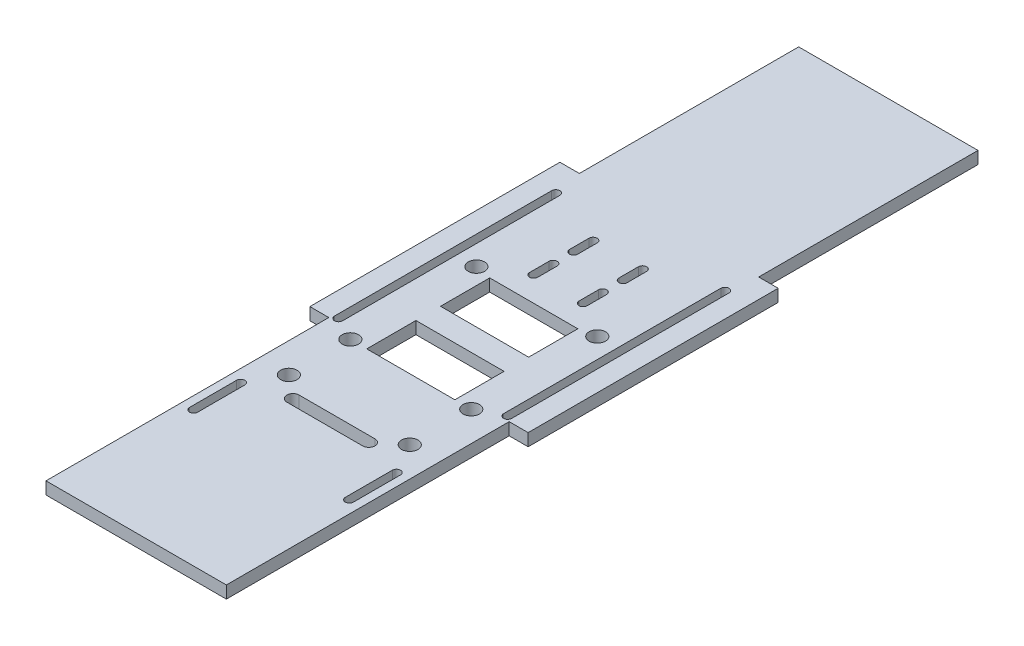
SolidWorks part; units mm, degrees
ref_plane "Front Plane" through (0, 0, 0) normal (0, 0, 1) x (1, 0, 0)
ref_plane "Top Plane" through (0, 0, 0) normal (0, 1, 0) x (1, 0, 0)
ref_plane "Right Plane" through (0, 0, 0) normal (1, 0, 0) x (0, 0, -1)
sketch "Sketch1" plane through (0, 0, 0) normal (0, 1, 0) x (1, 0, 0)
  line L1 (9.5525, -5.1674) -> (51.8197, -5.1674)
  line L2 (9.5525, -5.1674) -> (9.5525, 43.2514)
  line L3 (9.5525, 43.2514) -> (51.8197, 43.2514)
  line L4 (51.8197, -5.1674) -> (51.8197, 43.2514)
  line L5 (13.3228, 43.2514) -> (48.0494, 43.2514)
  line L6 (13.3228, 43.2514) -> (13.3228, 85.717)
  line L7 (13.3228, 85.717) -> (48.0494, 85.717)
  line L8 (48.0494, 43.2514) -> (48.0494, 85.717)
  line L9 (22.1533, -6.7549) -> (39.2189, -6.7549)
  line L10 (13.2236, -5.1674) -> (48.1486, -5.1674)
  line L11 (13.2236, -5.1674) -> (13.2236, -59.9361)
  line L12 (13.2236, -59.9361) -> (48.1486, -59.9361)
  line L13 (48.1486, -5.1674) -> (48.1486, -59.9361)
  line L14 (22.1533, -6.7549) -> (22.1533, 2.7701)
  line L15 (22.1533, 2.7701) -> (39.2189, 2.7701)
  line L16 (39.2189, -6.7549) -> (39.2189, 2.7701)
  line L20 (35.4697, 21.8201) -> (35.4697, 25.5901) construction
  line L21 (23.3439, -22.233) -> (38.0283, -22.233) construction
  line L22 (34.676, 21.8201) -> (34.676, 25.5901)
  line L23 (36.2635, 21.8201) -> (36.2635, 25.5901)
  line L24 (47.0572, -4.3736) -> (47.0572, 37.6951) construction
  line L25 (23.3439, -21.0424) -> (38.0283, -21.0424)
  line L26 (23.3439, -23.4236) -> (38.0283, -23.4236)
  line L27 (22.1533, 7.5326) -> (39.2189, 7.5326)
  line L28 (46.2635, -4.3736) -> (46.2635, 37.6951)
  line L29 (47.851, -4.3736) -> (47.851, 37.6951)
  line L30 (22.1533, 7.5326) -> (22.1533, 17.0576)
  line L31 (22.1533, 17.0576) -> (39.2189, 17.0576)
  line L32 (39.2189, 7.5326) -> (39.2189, 17.0576)
  line L33 (45.7674, -33.7424) -> (45.7674, -24.6143) construction
  line L34 (30.6861, 85.717) -> (30.6861, -59.9361)
  line L35 (44.9736, -33.7424) -> (44.9736, -24.6143)
  line L36 (46.5611, -33.7424) -> (46.5611, -24.6143)
  line L37 (35.4697, 29.5588) -> (35.4697, 33.3287) construction
  line L38 (34.676, 29.5588) -> (34.676, 33.3287)
  line L39 (36.2635, 29.5588) -> (36.2635, 33.3287)
  line L40 (25.9025, 29.5588) -> (25.9025, 33.3287) construction
  line L41 (26.6963, 29.5588) -> (26.6963, 33.3287)
  line L42 (25.1088, 29.5588) -> (25.1088, 33.3287)
  line L43 (25.9025, 21.8201) -> (25.9025, 25.5901) construction
  line L44 (26.6963, 21.8201) -> (26.6963, 25.5901)
  line L45 (25.1088, 21.8201) -> (25.1088, 25.5901)
  line L46 (14.315, -4.3736) -> (14.315, 37.6951) construction
  line L47 (15.1088, -4.3736) -> (15.1088, 37.6951)
  line L48 (13.5213, -4.3736) -> (13.5213, 37.6951)
  line L49 (15.6049, -33.7424) -> (15.6049, -24.6143) construction
  line L50 (16.3986, -33.7424) -> (16.3986, -24.6143)
  line L51 (14.8111, -33.7424) -> (14.8111, -24.6143)
  circle A0 centre (42.3939, -6.7549) radius 1.5875
  arc A1 (34.676, 21.8201) -> (36.2635, 21.8201) centre (35.4697, 21.8201) ccw
  arc A2 (36.2635, 25.5901) -> (34.676, 25.5901) centre (35.4697, 25.5901) ccw
  arc A3 (23.3439, -21.0424) -> (23.3439, -23.4236) centre (23.3439, -22.233) ccw
  arc A4 (38.0283, -23.4236) -> (38.0283, -21.0424) centre (38.0283, -22.233) ccw
  arc A5 (46.2635, -4.3736) -> (47.851, -4.3736) centre (47.0572, -4.3736) ccw
  arc A6 (47.851, 37.6951) -> (46.2635, 37.6951) centre (47.0572, 37.6951) ccw
  arc A7 (44.9736, -33.7424) -> (46.5611, -33.7424) centre (45.7674, -33.7424) ccw
  arc A8 (46.5611, -24.6143) -> (44.9736, -24.6143) centre (45.7674, -24.6143) ccw
  arc A9 (34.676, 29.5588) -> (36.2635, 29.5588) centre (35.4697, 29.5588) ccw
  arc A10 (36.2635, 33.3287) -> (34.676, 33.3287) centre (35.4697, 33.3287) ccw
  circle A11 centre (42.3939, 17.6529) radius 1.5875
  circle A12 centre (42.3939, -18.6611) radius 1.5875
  arc A13 (26.6963, 29.5588) -> (25.1088, 29.5588) centre (25.9025, 29.5588) cw
  arc A14 (25.1088, 33.3287) -> (26.6963, 33.3287) centre (25.9025, 33.3287) cw
  arc A15 (26.6963, 21.8201) -> (25.1088, 21.8201) centre (25.9025, 21.8201) cw
  arc A16 (25.1088, 25.5901) -> (26.6963, 25.5901) centre (25.9025, 25.5901) cw
  circle A17 centre (18.9783, 17.6529) radius 1.5875
  arc A18 (15.1088, -4.3736) -> (13.5213, -4.3736) centre (14.315, -4.3736) cw
  arc A19 (13.5213, 37.6951) -> (15.1088, 37.6951) centre (14.315, 37.6951) cw
  circle A20 centre (18.9783, -6.7549) radius 1.5875
  circle A21 centre (18.9783, -18.6611) radius 1.5875
  arc A22 (16.3986, -33.7424) -> (14.8111, -33.7424) centre (15.6049, -33.7424) cw
  arc A23 (14.8111, -24.6143) -> (16.3986, -24.6143) centre (15.6049, -24.6143) cw
  point P8 (30.6861, 43.2514)
  point P9 (30.6861, -5.1674)
  point P18 (22.1533, -22.233)
  point P21 (36.2635, 23.7051)
  point P24 (35.4697, 23.7051)
  point P32 (30.6861, -22.233)
  point P39 (30.6861, -6.7549)
  point P40 (47.0572, 16.6607)
  point P46 (45.7674, -29.1783)
  point P51 (30.6861, 7.5326)
  point P53 (35.4697, 21.0264)
  point P59 (0, 0)
  point P60 (0, 0)
  point P63 (29.506, 42.1053)
  point P64 (35.4697, 31.4438)
  point P69 (28.7122, 39.4266)
  point P70 (0, 0)
  point P71 (0, 0)
  point P72 (35.4697, 28.7651)
  point P73 (35.4697, 26.3838)
  point P76 (0, 0)
  point P77 (0, 0)
  point P78 (0, 0)
  point P81 (0, 0)
  point P82 (41.0049, -15.5365)
  point P83 (39.2189, -22.233)
  point P86 (25.9025, 31.4438)
  point P93 (25.9025, 23.7051)
  point P102 (14.315, 16.6607)
  point P113 (15.6049, -29.1783)
  dimension "D9" = 3.175
  dimension "D11" = 1.5875
  dimension "D13" = 17.0656
  dimension "D10" = 3.7699
  dimension "D20" = 3.9688
  dimension "D25" = 1.1906
  dimension "D27" = 21.2328
  dimension "D28" = 8.7312
  dimension "D1" = 48.4187
  dimension "D2" = 42.2672
  dimension "D3" = 42.4656
  dimension "D4" = 34.7266
  dimension "D5" = 54.7687
  dimension "D6" = 34.925
  dimension "D7" = 9.525
  dimension "D8" = 17.0656
  dimension "D12" = 2.3813
  dimension "D14" = 1.5875
  dimension "D15" = 42.0687
  dimension "D16" = 3.9688
  dimension "D17" = 3.175
  dimension "D18" = 14.2875
  dimension "D19" = 4.7625
  dimension "D21" = 10
  dimension "D22" = 1.5875
  dimension "D23" = 1.5875
  dimension "D24" = 9.1281
  dimension "D26" = 2.3813
extrude "Boss-Extrude2" add sketch "Sketch1" along normal mid plane 2.3813 contours L1 A20 L10 L11 L12 L34 L26 A3 L25 L9 L14 A21 L51 A23 L50 A22 | A4 L26 L34 L12 L13 L1 L10 A0 L16 L9 L25 A12 A8 L36 A7 L35 | L48 A19 L47 A18 L10 L1 L14 L15 L34 L27 L30 L31 L3 L2 L45 A16 L44 A15 L42 A14 L41 A13 A17 | A6 L29 A5 L1 L4 L3 L5 L34 L31 L32 L27 L15 L16 L10 L28 A11 A10 L39 A9 L38 A2 L23 A1 L22 | L34 L7 L6 L3 | L7 L34 L5 L8
